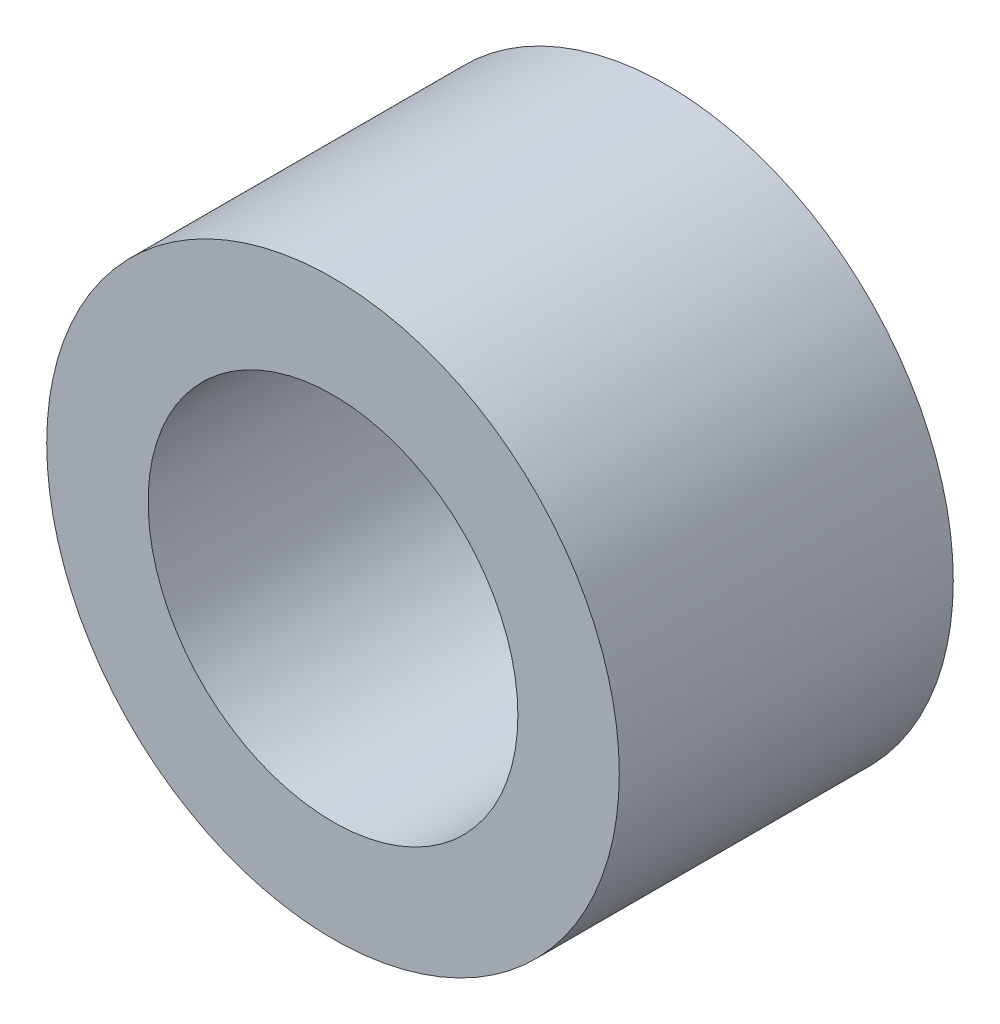
SolidWorks part; units mm, degrees
ref_plane "Front Plane" through (0, 0, 0) normal (0, 0, 1) x (1, 0, 0)
ref_plane "Top Plane" through (0, 0, 0) normal (0, 1, 0) x (1, 0, 0)
ref_plane "Right Plane" through (0, 0, 0) normal (1, 0, 0) x (0, 0, -1)
sketch "Sketch1" plane through (0, 0, 0) normal (0, 0, 1) x (1, 0, 0)
  circle A0 centre (0, 0) radius 24
  circle A1 centre (0, 0) radius 15.5
  dimension "D1" = 48
  dimension "D2" = 31
extrude "Boss-Extrude1" add sketch "Sketch1" along normal blind 28
